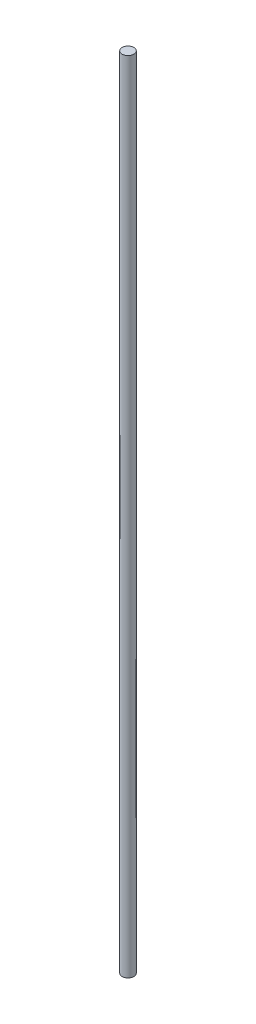
SolidWorks part; units mm, degrees
material "Balsa"
ref_plane "Front Plane" through (0, 0, 0) normal (0, 0, 1) x (1, 0, 0)
ref_plane "Top Plane" through (0, 0, 0) normal (0, 1, 0) x (1, 0, 0)
ref_plane "Right Plane" through (0, 0, 0) normal (1, 0, 0) x (0, 0, -1)
sketch "Sketch1" plane through (0, 0, 0) normal (0, 1, 0) x (1, 0, 0)
  circle A0 centre (0, 0) radius 4
extrude "Boss-Extrude1" add sketch "Sketch1" along normal mid plane 544
